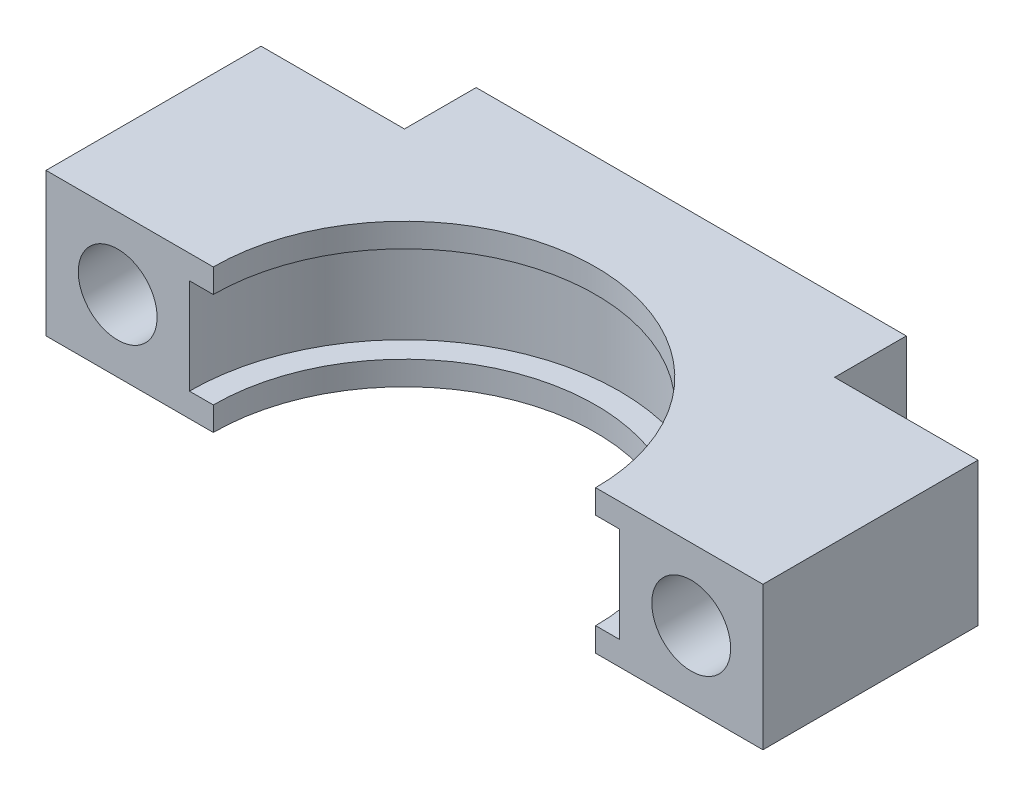
SolidWorks part; units mm, degrees
ref_plane "前视基准面" through (0, 0, 0) normal (0, 0, 1) x (1, 0, 0)
ref_plane "上视基准面" through (0, 0, 0) normal (0, 1, 0) x (1, 0, 0)
ref_plane "右视基准面" through (0, 0, 0) normal (1, 0, 0) x (0, 0, -1)
sketch "草图1" plane through (0, 0, 0) normal (0, 1, 0) x (1, 0, 0)
  line L0 (0, 0) -> (0, 6) construction
  line L1 (-15, 12) -> (15, 12)
  line L2 (-15, 12) -> (-15, 0)
  line L3 (-15, 0) -> (15, 0)
  line L4 (15, 12) -> (15, 0)
  line L5 (-15, 12) -> (15, 0) construction
  line L6 (-15, 0) -> (15, 12) construction
  point P0 (0, 6)
  dimension "D1" = 30
  dimension "D2" = 12
extrude "凸台-拉伸1" add sketch "草图1" along normal blind 6
sketch "草图2" plane through (0, 0, 0) normal (0, 0, 1) x (1, 0, 0)
  line L0 (0, 0) -> (0, 6)
  line L1 (-15, 6) -> (15, 6) construction
  line L2 (0, 6) -> (-8, 6)
  line L3 (-8, 6) -> (-8, 5)
  line L4 (-8, 5) -> (-9, 5)
  line L5 (-9, 5) -> (-9, 1)
  line L6 (-9, 1) -> (-8, 1)
  line L7 (-8, 1) -> (-8, 0)
  line L8 (-15, 0) -> (15, 0) construction
  line L9 (-8, 0) -> (0, 0)
  line L10 (-9, 3) -> (0, 3) construction
  dimension "D1" = 8
  dimension "D2" = 4
  dimension "D3" = 9
revolve "切除-旋转1" cut sketch "草图2" angle 360 about L0
sketch "草图3" plane through (0, 0, -12) normal (0, 0, -1) x (-1, 0, 0)
  line L0 (-15, 0) -> (15, 0) construction
  line L1 (-15, 6) -> (-9, 6)
  line L2 (-15, 6) -> (-15, 0)
  line L3 (-15, 0) -> (-9, 0)
  line L4 (-9, 6) -> (-9, 0)
  dimension "D1" = 6
extrude "切除-拉伸1" cut sketch "草图3" against normal blind 3
sketch "草图4" plane through (0, 0, -9) normal (0, 0, -1) x (-1, 0, 0)
  line L0 (-15, 6) -> (-9, 0) construction
  circle A0 centre (-12, 3) radius 1.65
  dimension "D1" = 3.3
extrude "切除-拉伸2" cut sketch "草图4" against normal up to next
mirror "镜向1" about plane through (0, 0, 0) normal (1, 0, 0) of "切除-拉伸2", "切除-拉伸1"
